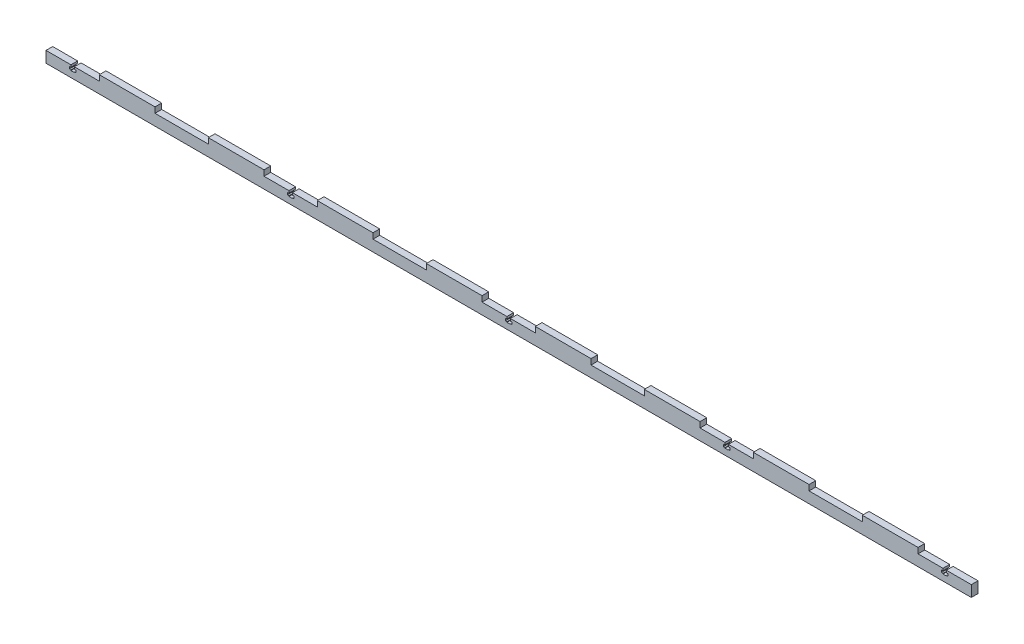
SolidWorks part; units mm, degrees
ref_plane "Płaszczyzna przednia" through (0, 0, 0) normal (0, 0, 1) x (1, 0, 0)
ref_plane "Płaszczyzna górna" through (0, 0, 0) normal (0, 1, 0) x (1, 0, 0)
ref_plane "Płaszczyzna prawa" through (0, 0, 0) normal (1, 0, 0) x (0, 0, -1)
sketch "Szkic1" plane through (0, 0, 0) normal (0, 0, 1) x (1, 0, 0)
  line L1 (0, 0) -> (830, 0)
  line L2 (0, 0) -> (0, 16)
  line L3 (0, 16) -> (830, 16)
  line L4 (830, 0) -> (830, 16)
  line L6 (845, 28) -> (845, -10) construction
  dimension "D1" = 15
  dimension "D2" = 16
extrude "Dodanie-wyciągnięcie1" add sketch "Szkic1" along normal blind 6
sketch "Szkic2" plane through (0, 16, 0) normal (0, 1, 0) x (1, 0, 0)
  line L0 (830, -6) -> (830, 0) construction
  line L1 (830, 0) -> (0, 0) construction
  line L2 (830, -6) -> (782.222, -6)
  line L3 (830, -6) -> (830, 0)
  line L4 (830, 0) -> (782.222, 0)
  line L5 (782.222, -6) -> (782.222, 0)
  dimension "D1" = 47.778
  dimension "D2" = 0
extrude "Wytnij-wyciągnięcie1" cut sketch "Szkic2" against normal blind 6
pattern_linear "Szyk liniowy1" count 9 spacing 97.778 along (-1, 0, 0) of "Wytnij-wyciągnięcie1"
sketch "Szkic4" plane through (0, 0, 6) normal (0, 0, 1) x (1, 0, 0)
  line L0 (0, 10) -> (47.776, 10) construction
  line L1 (22.34, 10) -> (25.44, 10)
  line L2 (22.34, 10) -> (22.34, 8)
  line L3 (22.34, 5.5) -> (25.44, 5.5)
  line L4 (25.44, 10) -> (25.44, 8)
  line L5 (22.34, 6) -> (22.34, 5.5)
  line L6 (20.965, 6) -> (22.34, 6)
  line L7 (20.965, 6) -> (20.965, 8)
  line L8 (20.965, 8) -> (22.34, 8)
  line L9 (26.815, 6) -> (26.815, 8)
  line L10 (25.44, 6) -> (26.815, 6)
  line L11 (25.44, 8) -> (26.815, 8)
  line L12 (25.44, 6) -> (25.44, 5.5)
  line L13 (0, 10) -> (0, 0) construction
  point P14 (23.89, 10)
  dimension "D1" = 3.1
  dimension "D2" = 4.5
  dimension "D3" = 0.5
  dimension "D4" = 5.85
  dimension "D5" = 1.375
  dimension "D6" = 2
  dimension "D7" = 23.89
extrude "Wytnij-wyciągnięcie2" cut sketch "Szkic4" against normal blind 6
pattern_linear "Szyk liniowy2" count 5 spacing 195.56 along (1, 0, 0) of "Wytnij-wyciągnięcie2"
sketch "Szkic5" plane through (0, 0, 6) normal (0, 0, 1) x (1, 0, 0)
  line L0 (47.776, 16) -> (47.776, 15)
  line L1 (47.776, 16) -> (782.222, 16)
  line L2 (47.776, 15) -> (782.222, 15)
  line L3 (782.222, 16) -> (782.222, 15)
  line L4 (47.776, 10) -> (47.776, 16) construction
  line L5 (782.222, 10) -> (782.222, 16) construction
  dimension "D1" = 1
  dimension "D2" = 0
extrude "Wytnij-wyciągnięcie3" cut sketch "Szkic5" against normal blind 10
equation "\"tolerancja_wpusy\"=0.2"
equation "\"dlugosc_wpustu_duzy\"=20"
equation "\"srednica_otworu_M3\"=3.1"
equation "\"szerokosc_nogi_T\"=3.1"
equation "\"dlugosc_T_30\"=11"
equation "\"grubosc_na_nakretke_kwadrat\"=2"
equation "\"szerokosc_na_nakretke_kwadrat\"=5.85"
equation "\"wyokosc_nadstawki_T\"=0.5"
equation "\"dlugosc_T_20_6\"=14"
equation "\"D1@Szkic4\"=\"szerokosc_nogi_T\""
equation "\"D3@Szkic4\"=\"wyokosc_nadstawki_T\""
equation "\"D4@Szkic4\"=\"szerokosc_na_nakretke_kwadrat\""
equation "\"D5@Szkic4\"=(\"szerokosc_na_nakretke_kwadrat\"-\"szerokosc_nogi_T\")/2"
equation "\"D6@Szkic4\"=\"grubosc_na_nakretke_kwadrat\""
